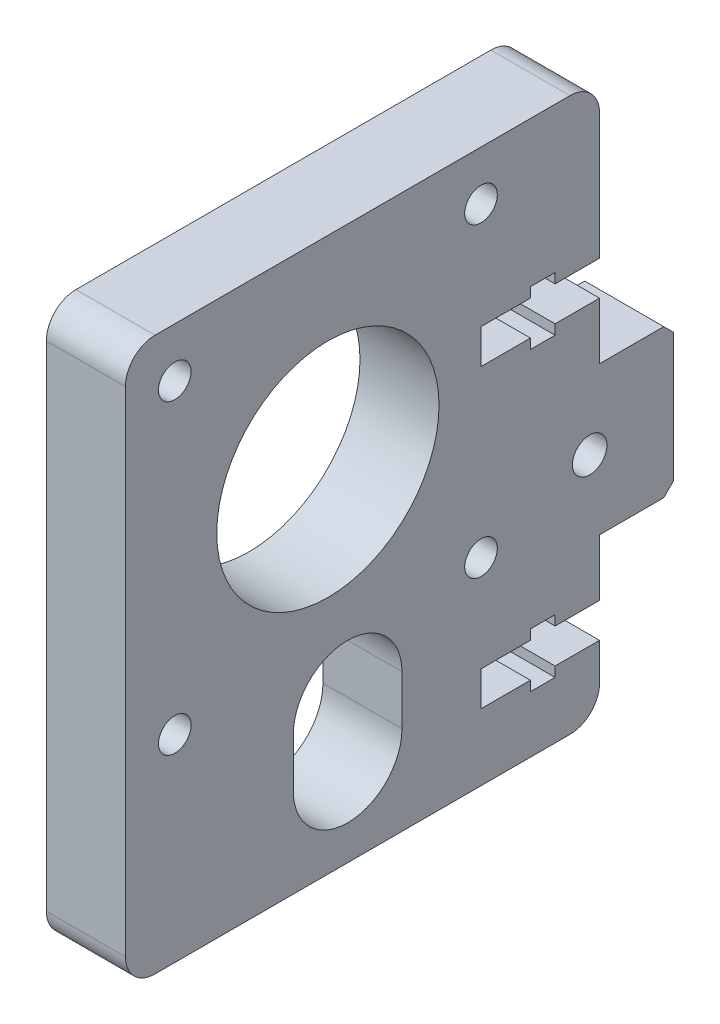
SolidWorks part; units mm, degrees
ref_plane "Front Plane" through (0, 0, 0) normal (0, 0, 1) x (1, 0, 0)
ref_plane "Top Plane" through (0, 0, 0) normal (0, 1, 0) x (1, 0, 0)
ref_plane "Right Plane" through (0, 0, 0) normal (1, 0, 0) x (0, 0, -1)
sketch "Sketch1" plane through (0, 0, 0) normal (1, 0, 0) x (0, 0, -1)
  line L0 (53.0323, 11.7244) -> (53.0323, 7.9744)
  line L1 (50.0323, 4.9744) -> (8.0323, 4.9744)
  line L2 (5.0323, 7.9744) -> (5.0323, 57.9744)
  line L3 (8.0323, 60.9744) -> (50.0323, 60.9744)
  line L4 (53.0323, 57.9744) -> (53.0323, 45.2244)
  line L5 (53.0323, 45.2244) -> (48.5323, 45.2244)
  line L6 (48.5323, 45.2244) -> (48.5323, 46.2244)
  line L7 (48.5323, 46.2244) -> (46.0323, 46.2244)
  line L8 (46.0323, 46.2244) -> (46.0323, 45.2244)
  line L9 (46.0323, 45.2244) -> (41.0323, 45.2244)
  line L10 (41.0323, 45.2244) -> (41.0323, 41.7244)
  line L11 (41.0323, 41.7244) -> (46.0323, 41.7244)
  line L12 (46.0323, 41.7244) -> (46.0323, 40.7244)
  line L13 (46.0323, 40.7244) -> (48.5323, 40.7244)
  line L14 (48.5323, 40.7244) -> (48.5323, 41.7244)
  line L15 (48.5323, 41.7244) -> (53.0323, 41.7244)
  line L16 (53.0323, 41.7244) -> (53.0323, 35.9744)
  line L17 (53.0323, 35.9744) -> (59.5323, 35.9744)
  line L18 (59.5323, 35.9744) -> (60.5323, 34.9744)
  line L19 (60.5323, 34.9744) -> (60.5323, 21.9744)
  line L20 (60.5323, 21.9744) -> (59.5323, 20.9744)
  line L21 (59.5323, 20.9744) -> (53.0323, 20.9744)
  line L22 (53.0323, 20.9744) -> (53.0323, 15.2244)
  line L23 (53.0323, 15.2244) -> (48.5323, 15.2244)
  line L24 (48.5323, 15.2244) -> (48.5323, 16.2244)
  line L25 (48.5323, 16.2244) -> (46.0323, 16.2244)
  line L26 (46.0323, 16.2244) -> (46.0323, 15.2244)
  line L27 (46.0323, 15.2244) -> (41.0323, 15.2244)
  line L28 (41.0323, 15.2244) -> (41.0323, 11.7244)
  line L29 (41.0323, 11.7244) -> (46.0323, 11.7244)
  line L30 (46.0323, 11.7244) -> (46.0323, 10.7244)
  line L31 (46.0323, 10.7244) -> (48.5323, 10.7244)
  line L32 (48.5323, 10.7244) -> (48.5323, 11.7244)
  line L33 (48.5323, 11.7244) -> (53.0323, 11.7244)
  line L34 (22.0323, 18.9744) -> (22.0323, 13.9744)
  line L35 (33.0323, 13.9744) -> (33.0323, 18.9744)
  arc A0 (50.0323, 4.9744) -> (53.0323, 7.9744) centre (50.0323, 7.9744) ccw
  arc A1 (5.0323, 7.9744) -> (8.0323, 4.9744) centre (8.0323, 7.9744) ccw
  arc A2 (8.0323, 60.9744) -> (5.0323, 57.9744) centre (8.0323, 57.9744) ccw
  arc A3 (53.0323, 57.9744) -> (50.0323, 60.9744) centre (50.0323, 57.9744) ccw
  circle A4 centre (41.0323, 55.9744) radius 1.65
  circle A5 centre (10.0323, 55.9744) radius 1.65
  circle A6 centre (41.0323, 24.9744) radius 1.65
  circle A7 centre (10.0323, 24.9744) radius 1.65
  arc A8 (22.0323, 13.9744) -> (33.0323, 13.9744) centre (27.5323, 13.9744) ccw
  arc A9 (33.0323, 18.9744) -> (22.0323, 18.9744) centre (27.5323, 18.9744) ccw
  circle A10 centre (52.0323, 28.4744) radius 1.75
extrude "Extrude1" add sketch "Sketch1" along normal blind 8
sketch "Sketch2" plane through (0, 0, -41.0323) normal (0, 0, -1) x (-1, 0, 0)
  line L0 (0, 45.2244) -> (-8, 41.7244)
  circle A0 centre (-4, 43.4744) radius 1
  dimension "D1" = 2
extrude "Extrude2" cut sketch "Sketch2" against normal blind 1 contours A0
sketch "Sketch3" plane through (0, 0, -41.0323) normal (0, 0, -1) x (-1, 0, 0)
  line L0 (0, 15.2244) -> (-8, 11.7244)
  circle A0 centre (-4, 13.4744) radius 1
  dimension "D1" = 2
extrude "Extrude3" cut sketch "Sketch3" against normal blind 1 contours A0
sketch "Sketch4" plane through (8, 0, 0) normal (1, 0, 0) x (0, 0, -1)
  line L0 (10.0323, 55.9744) -> (41.0323, 24.9744) construction
  circle A0 centre (25.5323, 40.4744) radius 11.25
  dimension "D1" = 22.5
extrude "Extrude4" cut sketch "Sketch4" against normal blind 10
